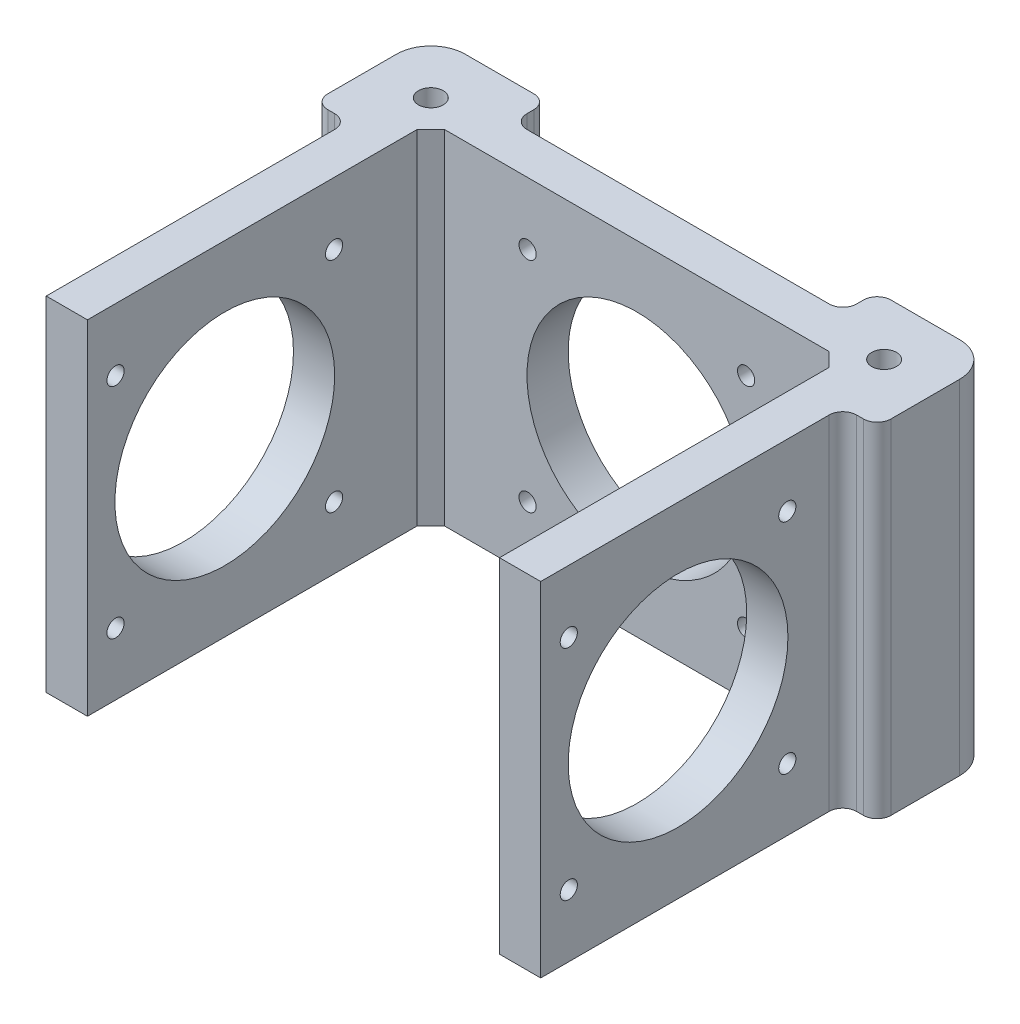
SolidWorks part; units mm, degrees
ref_plane "Front Plane" through (0, 0, 0) normal (0, 0, 1) x (1, 0, 0)
ref_plane "Top Plane" through (0, 0, 0) normal (0, 1, 0) x (1, 0, 0)
ref_plane "Right Plane" through (0, 0, 0) normal (1, 0, 0) x (0, 0, -1)
sketch "Sketch1" plane through (0, 0, 0) normal (0, 1, 0) x (1, 0, 0)
  line L0 (-12, -43.4583) -> (-6, -43.4583)
  line L1 (-6, -43.4583) -> (-6, 6.5417)
  line L10 (-6, 6.5417) -> (54, 6.5417)
  line L11 (54, 6.5417) -> (54, -43.4583)
  line L12 (54, -43.4583) -> (60, -43.4583)
  line L13 (60, -43.4583) -> (60, 12.5417)
  line L14 (60, 12.5417) -> (-12, 12.5417)
  line L15 (-12, 12.5417) -> (-12, -43.4583)
  line L16 (13.117, 6.5417) -> (13.117, 12.5417) construction
  dimension "D1" = 6
  dimension "D2" = 50
  dimension "D3" = 60
extrude "Boss-Extrude1" add sketch "Sketch1" along normal blind 50
sketch "Sketch2" plane through (-6, 0, 0) normal (1, 0, 0) x (0, 0, -1)
  line L0 (-43.4583, 50) -> (-43.4583, 0) construction
  circle A0 centre (-23.4583, 25) radius 16
  dimension "D1" = 32
  dimension "D2" = 20
extrude "Cut-Extrude1" cut sketch "Sketch2" against normal through all both and the other way through all
sketch "Sketch3" plane through (0, 0, -6.5417) normal (0, 0, 1) x (1, 0, 0)
  line L0 (-6, 0) -> (54, 50) construction
  line L1 (54, 0) -> (-6, 50) construction
  circle A0 centre (24, 25) radius 16
  dimension "D1" = 32
extrude "Cut-Extrude2" cut sketch "Sketch3" against normal through all
hole_wizard "Tap Drill for M3 Tap1" positions "Sketch4" profile "Sketch6" hole size "M3" standard "DIN" end condition through all
sketch "Sketch4" plane through (60, 0, 0) normal (1, 0, 0) x (0, 0, -1)
  line L0 (-23.4583, 25) -> (-39.3682, 40.9099) construction
  circle A0 centre (-23.4583, 25) radius 22.5 construction
  point P7 (-39.3682, 40.9099)
  point P17 (-7.5484, 40.9099)
  point P18 (-7.5484, 9.0901)
  point P19 (-39.3682, 9.0901)
  dimension "D1" = 45
  dimension "D2" = 4
sketch "Sketch6" plane through (60, 9.0901, 39.3682) normal (0, 1, 0) x (0, 0, -1)
  line L0 (0, 0) -> (0, 72)
  line L1 (0, 72) -> (1.25, 72)
  line L2 (1.25, 72) -> (1.25, 0)
  line L5 (1.25, 0) -> (0, 0)
  line L11 (0, -6.35) -> (0, 107.95) construction
  dimension "Thru Hole Dia." = 2.5
  dimension "Thru Hole Depth" = 72
hole_wizard "Tap Drill for M3 Tap2" positions "Sketch7" profile "Sketch8" hole size "M3" standard "DIN" end condition through all
sketch "Sketch7" plane through (0, 0, -12.5417) normal (0, 0, -1) x (-1, 0, 0)
  line L0 (-24, 25) -> (-39.9099, 40.9099) construction
  circle A0 centre (-24, 25) radius 22.5 construction
  point P6 (-39.9099, 40.9099)
  point P16 (-8.0901, 40.9099)
  point P17 (-8.0901, 9.0901)
  point P18 (-39.9099, 9.0901)
  dimension "D1" = 45
  dimension "D2" = 4
sketch "Sketch8" plane through (39.9099, 9.0901, -12.5417) normal (1, 0, 0) x (0, 1, 0)
  line L0 (0, 0) -> (0, 56)
  line L1 (0, 56) -> (1.25, 56)
  line L2 (1.25, 56) -> (1.25, 0)
  line L5 (1.25, 0) -> (0, 0)
  line L11 (0, -6.35) -> (0, 107.95) construction
  dimension "Thru Hole Dia." = 2.5
  dimension "Thru Hole Depth" = 56
chamfer "Chamfer1" distance 2 angle 45 2 edges at (54, 25, -6.5417) (-6, 25, -6.5417)
sketch "Sketch9" plane through (0, 50, 0) normal (0, 1, 0) x (1, 0, 0)
  line L0 (-12, 0.5417) -> (-17, 0.5417)
  line L1 (-12, 12.5417) -> (-12, -43.4583) construction
  line L2 (-17, 0.5417) -> (-17, 17.5417)
  line L3 (-17, 17.5417) -> (0, 17.5417)
  line L4 (65, 17.5417) -> (65, 0.5417)
  line L5 (65, 0.5417) -> (60, 0.5417)
  line L6 (60, -43.4583) -> (60, 12.5417) construction
  line L7 (60, 0.5417) -> (60, 12.5417)
  line L8 (60, 12.5417) -> (48, 12.5417)
  line L9 (-12, 12.5417) -> (-12, 0.5417)
  line L10 (0, 17.5417) -> (0, 12.5417)
  line L11 (48, 17.5417) -> (48, 12.5417)
  line L12 (48, 17.5417) -> (65, 17.5417)
  line L13 (0, 12.5417) -> (-12, 12.5417)
  dimension "D1" = 12
  dimension "D2" = 5
  dimension "D3" = 5
extrude "Boss-Extrude2" add sketch "Sketch9" against normal up to surface (50 mm away) up to face at (24, 0, 12.6583)
fillet "Fillet1" radius 2 8 edges at (65, 25, -0.5417) (60, 25, -0.5417) (48, 25, -17.5417) (48, 25, -12.5417) (0, 25, -12.5417) (0, 25, -17.5417) (-17, 25, -0.5417) (-12, 25, -0.5417)
fillet "Fillet2" radius 5 2 edges at (-17, 25, -17.5417) (65, 25, -17.5417)
hole_wizard "M3 Clearance Hole1" positions "Sketch10" profile "Sketch11" hole size "M3" standard "DIN" end condition through all
sketch "Sketch10" plane through (0, 50, 0) normal (0, 1, 0) x (1, 0, 0)
  line L0 (-9, -43.4583) -> (-9, 9.5417)
  line L1 (-12, -43.4583) -> (-6, -43.4583) construction
  line L2 (-9, 9.5417) -> (57, 9.5417)
  line L3 (57, 9.5417) -> (57, -43.4583)
  line L4 (54, -43.4583) -> (60, -43.4583) construction
  line L6 (27.8491, 6.5417) -> (27.8491, 9.5417) construction
  line L7 (-4, 6.5417) -> (52, 6.5417) construction
  line L8 (27.8491, 9.5417) -> (27.8491, 12.5417) construction
  line L9 (46, 12.5417) -> (2, 12.5417) construction
  point P0 (-9, 9.5417)
  point P2 (57, 9.5417)
sketch "Sketch11" plane through (-9, 50, -9.5417) normal (1, 0, 0) x (0, 0, 1)
  line L0 (0, 0) -> (0, 50)
  line L1 (0, 50) -> (1.8, 50)
  line L2 (1.8, 50) -> (1.8, 0)
  line L5 (1.8, 0) -> (0, 0)
  line L11 (0, -6.35) -> (0, 107.95) construction
  dimension "Thru Hole Dia." = 3.6
  dimension "Thru Hole Depth" = 50
